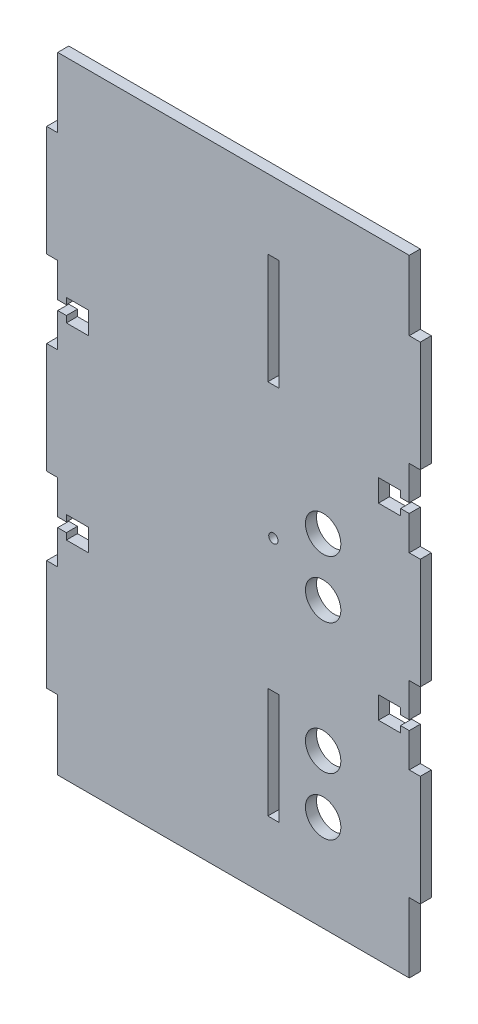
SolidWorks part; units mm, degrees
ref_plane "Plan de face" through (0, 0, 0) normal (0, 0, 1) x (1, 0, 0)
ref_plane "Plan de dessus" through (0, 0, 0) normal (0, 1, 0) x (1, 0, 0)
ref_plane "Plan de droite" through (0, 0, 0) normal (1, 0, 0) x (0, 0, -1)
sketch "Esquisse1" plane through (0, 0, 0) normal (0, 0, 1) x (1, 0, 0)
  line L0 (0, -3.53) -> (0, -35)
  line L1 (0, -35) -> (-5, -35)
  line L2 (-5, -35) -> (-5, -85)
  line L3 (-5, -85) -> (0, -85)
  line L4 (0, -85) -> (0, -100.4)
  line L5 (0, -120) -> (-5, -120)
  line L6 (-5, -120) -> (-5, -170)
  line L8 (-5, -60) -> (81.68, -60) construction
  line L9 (97.5, 0) -> (97.5, -290) construction
  line L10 (163.9185, -120) -> (163.9185, -170)
  line L11 (158.9185, -120) -> (163.9185, -120)
  line L12 (158.9185, -85) -> (158.9185, -100.4)
  line L13 (163.9185, -85) -> (158.9185, -85)
  line L14 (163.9185, -35) -> (163.9185, -85)
  line L15 (158.9185, -35) -> (163.9185, -35)
  line L16 (158.9185, -3.53) -> (158.9185, -35)
  line L17 (0, -170) -> (-5, -170)
  line L18 (0, -205) -> (0, -189.6)
  line L19 (-5, -205) -> (0, -205)
  line L20 (-5, -255) -> (-5, -205)
  line L21 (0, -255) -> (-5, -255)
  line L22 (0, -286.47) -> (0, -255)
  line L23 (158.9185, -286.47) -> (158.9185, -255)
  line L27 (158.9185, -205) -> (158.9185, -189.6)
  line L28 (158.9185, -170) -> (163.9185, -170)
  line L30 (0, -104.6) -> (3.9185, -104.6)
  line L33 (0, -100.4) -> (3.9185, -100.4)
  line L42 (0, -104.6) -> (0, -120)
  line L45 (0, -3.53) -> (158.9185, -3.53)
  line L48 (0, -185.4) -> (3.9185, -185.4)
  line L56 (0, -189.6) -> (3.9185, -189.6)
  line L57 (0, -185.4) -> (0, -170)
  line L62 (158.9185, -189.6) -> (155, -189.6)
  line L65 (158.9185, -185.4) -> (155, -185.4)
  line L71 (158.9185, -104.6) -> (155, -104.6)
  line L79 (158.9185, -100.4) -> (155, -100.4)
  line L80 (158.9185, -104.6) -> (158.9185, -120)
  line L81 (158.9185, -185.4) -> (158.9185, -170)
  line L82 (95, -35) -> (100, -35)
  line L83 (95, -35) -> (95, -85)
  line L84 (95, -85) -> (100, -85)
  line L85 (100, -35) -> (100, -85)
  line L90 (95, -205) -> (100, -205)
  line L91 (95, -205) -> (95, -255)
  line L92 (95, -255) -> (100, -255)
  line L93 (100, -205) -> (100, -255)
  line L94 (0, -286.47) -> (158.9185, -286.47)
  line L95 (97.5, -145) -> (66.3125, -145) construction
  line L96 (100, -230) -> (140, -230) construction
  line L97 (155, -189.6) -> (155, -192.5)
  line L98 (155, -192.5) -> (145, -192.5)
  line L102 (145, -192.5) -> (145, -182.5)
  line L103 (155, -185.4) -> (155, -182.5)
  line L104 (155, -182.5) -> (145, -182.5)
  line L105 (155, -104.6) -> (155, -107.5)
  line L106 (155, -107.5) -> (145, -107.5)
  line L107 (145, -97.5) -> (145, -107.5)
  line L108 (155, -97.5) -> (145, -97.5)
  line L109 (155, -100.4) -> (155, -97.5)
  line L110 (79.4592, -286.47) -> (79.4592, -268.3036) construction
  line L111 (3.9185, -104.6) -> (3.9185, -107.5)
  line L112 (3.9185, -100.4) -> (3.9185, -97.5)
  line L113 (3.9185, -97.5) -> (13.9185, -97.5)
  line L114 (13.9185, -97.5) -> (13.9185, -107.5)
  line L115 (3.9185, -107.5) -> (13.9185, -107.5)
  line L116 (3.9185, -185.4) -> (3.9185, -182.5)
  line L117 (13.9185, -192.5) -> (13.9185, -182.5)
  line L118 (3.9185, -182.5) -> (13.9185, -182.5)
  line L119 (3.9185, -192.5) -> (13.9185, -192.5)
  line L120 (3.9185, -189.6) -> (3.9185, -192.5)
  line L121 (158.9185, -205) -> (163.9185, -205)
  line L122 (163.9185, -205) -> (163.9185, -255)
  line L123 (163.9185, -255) -> (158.9185, -255)
  circle A0 centre (97.5, -145) radius 2.1
  circle A10 centre (120, -132) radius 8
  circle A11 centre (120, -158) radius 8
  circle A12 centre (120, -217) radius 8
  circle A13 centre (120, -243) radius 8
  point P34 (163.9185, -145)
  dimension "D13" = 4.2
  dimension "D16" = 16
  dimension "D17" = 13
  dimension "D18" = 20
  dimension "D19" = 16
  dimension "D20" = 13
  dimension "D2" = 5
  dimension "D3" = 50
  dimension "D4" = 35
  dimension "D5" = 5
  dimension "D6" = 5
  dimension "D7" = 86.68
  dimension "D8" = 2.5
  dimension "D9" = 5
  dimension "D10" = 5
  dimension "D11" = 5
  dimension "D12" = 5
  dimension "D14" = 2.5
  dimension "D15" = 100
  dimension "D21" = 2.9
  dimension "D22" = 10
  dimension "D23" = 10
  dimension "D24" = 2.9
  dimension "D25" = 5
extrude "Boss.-Extru.1" add sketch "Esquisse1" along normal blind 5
